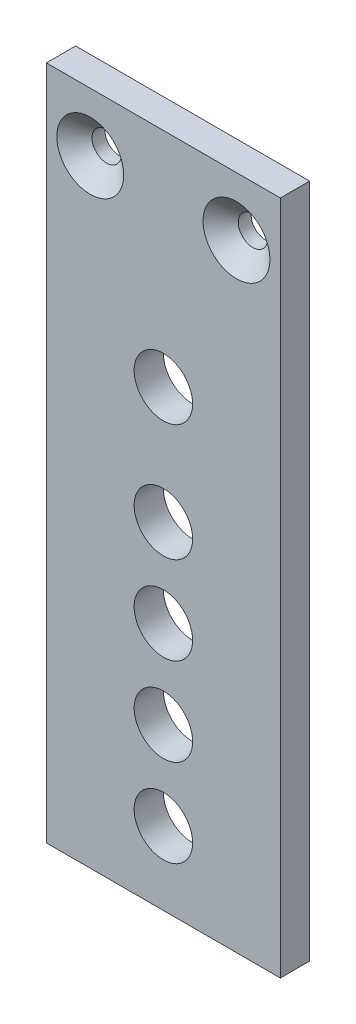
SolidWorks part; units mm, degrees
material "6061-T6 (SS)"
ref_plane "Front Plane" through (0, 0, 0) normal (0, 0, 1) x (1, 0, 0)
ref_plane "Top Plane" through (0, 0, 0) normal (0, 1, 0) x (1, 0, 0)
ref_plane "Right Plane" through (0, 0, 0) normal (1, 0, 0) x (0, 0, -1)
sketch "Sketch1" plane through (0, 0, 0) normal (0, 0, 1) x (1, 0, 0)
  line L0 (-25.4, -146.685) -> (25.4, -146.685)
  line L1 (-25.4, 0) -> (25.4, 0)
  line L2 (-25.4, 0) -> (-25.4, -146.685)
  line L4 (25.4, 0) -> (25.4, -146.685)
  circle A1 centre (0, -130.81) radius 6.35
  circle A2 centre (0, -111.76) radius 6.35
  circle A3 centre (0, -92.71) radius 6.35
  circle A4 centre (0, -73.66) radius 6.35
  circle A5 centre (-15.875, -12.7) radius 3.175
  circle A6 centre (15.875, -12.7) radius 3.175
  circle A7 centre (0, -48.26) radius 6.35
  point P18 (0, 0)
  dimension "D6" = 12.7
  dimension "D7" = 6.35
  dimension "D8" = 25.4
  dimension "D11" = 111.76
  dimension "D16" = 9.525
  dimension "D1" = 50.8
  dimension "D3" = 15.875
  dimension "D4" = 25.4
  dimension "D9" = 19.05
  dimension "D10" = 19.05
  dimension "D12" = 19.05
  dimension "D15" = 9.525
  dimension "D17" = 12.7
  dimension "D18" = 12.7
  dimension "D19" = 25.4
  dimension "D20" = 25.4
  dimension "D21" = 25.4
extrude "Boss-Extrude3" add sketch "Sketch1" along normal blind 6.35
chamfer "Chamfer1" distance 4.0894 angle 41 1 edges at (-12.7, -12.7, 6.35)
chamfer "Chamfer2" distance 4.0894 angle 41 1 edges at (19.05, -12.7, 6.35)
